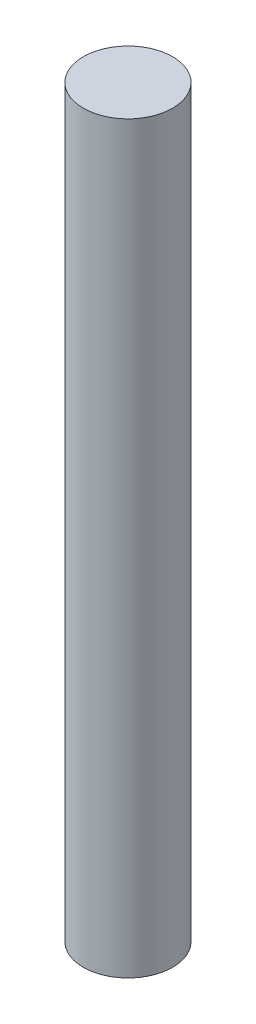
SolidWorks part; units mm, degrees
ref_plane "Front Plane" through (0, 0, 0) normal (0, 0, 1) x (1, 0, 0)
ref_plane "Top Plane" through (0, 0, 0) normal (0, 1, 0) x (1, 0, 0)
ref_plane "Right Plane" through (0, 0, 0) normal (1, 0, 0) x (0, 0, -1)
sketch "Sketch1" plane through (0, 0, 0) normal (0, 1, 0) x (1, 0, 0)
  circle A0 centre (0, 0) radius 1.5
  dimension "D1" = 3
extrude "Boss-Extrude1" add sketch "Sketch1" along normal blind 25
